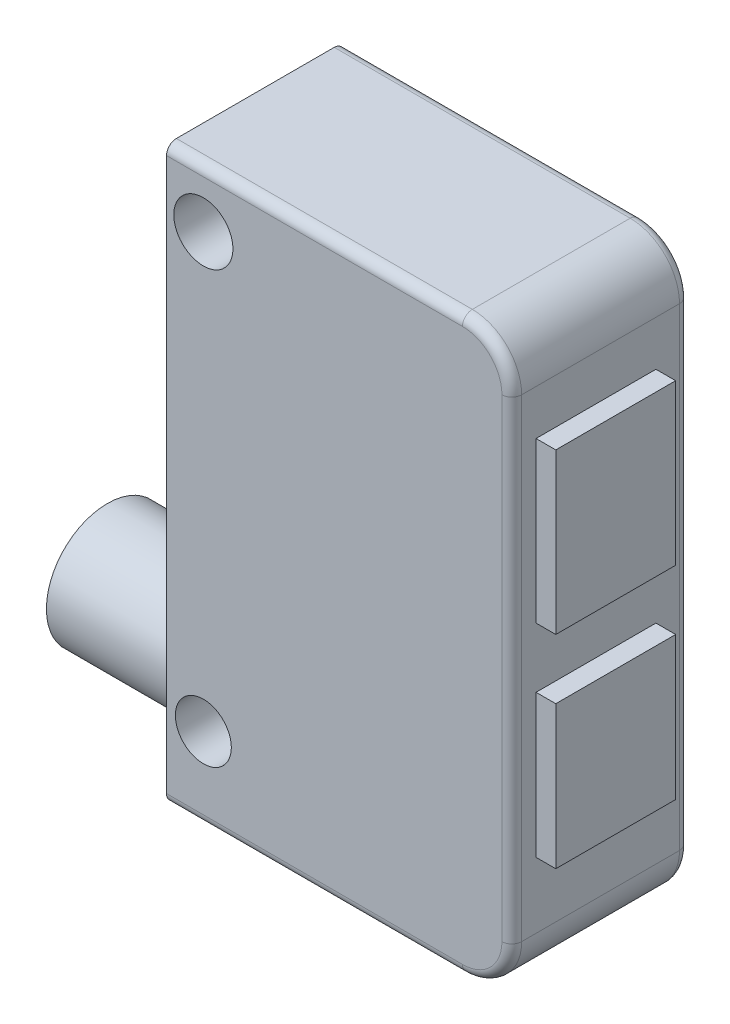
SolidWorks part; units mm, degrees
ref_plane "Alzado" through (0, 0, 0) normal (0, 0, 1) x (1, 0, 0)
ref_plane "Planta" through (0, 0, 0) normal (0, 1, 0) x (1, 0, 0)
ref_plane "Vista lateral" through (0, 0, 0) normal (1, 0, 0) x (0, 0, -1)
sketch "Croquis1" plane through (0, 0, 0) normal (0, 0, 1) x (1, 0, 0)
  line L1 (-17.5, 29) -> (17.5, 29)
  line L2 (-17.5, 29) -> (-17.5, -29)
  line L3 (-17.5, -29) -> (17.5, -29)
  line L4 (17.5, 29) -> (17.5, -29)
  line L5 (-17.5, 29) -> (17.5, -29) construction
  line L6 (-17.5, -29) -> (17.5, 29) construction
  point P0 (0, 0)
  dimension "D1" = 35
  dimension "D2" = 58
extrude "Saliente-Extruir1" add sketch "Croquis1" along normal blind 18
sketch "Croquis2" plane through (-17.5, 0, 0) normal (-1, 0, 0) x (0, 0, 1)
  circle A0 centre (8, -21.7144) radius 6.1719
extrude "Saliente-Extruir2" add sketch "Croquis2" along normal blind 16
fillet "Redondeo1" radius 5 2 edges at (17.5, -29, 9) (17.5, 29, 9)
fillet "Redondeo2" radius 1 10 edges at (-2.5, -29, 0) (16.0355, -27.5355, 0) (17.5, 0, 0) (16.0355, 27.5355, 0) (-2.5, -29, 18) (16.0355, -27.5355, 18) (17.5, 0, 18) (16.0355, 27.5355, 18) (-2.5, 29, 0) (-2.5, 29, 18)
sketch "Croquis3" plane through (0, 0, 18) normal (0, 0, 1) x (1, 0, 0)
  circle A0 centre (-13.7643, 23.1741) radius 2.9977
  circle A1 centre (-13.7643, -20.6814) radius 2.8355
extrude "Cortar-Extruir1" cut sketch "Croquis3" against normal blind 16
sketch "Croquis4" plane through (17.5, 0, 0) normal (1, 0, 0) x (0, 0, -1)
  line L1 (-15.5433, 3.2327) -> (-3.3915, 3.2327)
  line L2 (-15.5433, 3.2327) -> (-15.5433, 19.435)
  line L3 (-15.5433, 19.435) -> (-3.3915, 19.435)
  line L4 (-3.3915, 3.2327) -> (-3.3915, 19.435)
  line L5 (-15.5433, 3.2327) -> (-3.3915, 19.435) construction
  line L6 (-15.5433, 19.435) -> (-3.3915, 3.2327) construction
  line L7 (-15.5433, -17.3319) -> (-3.3915, -17.3319)
  line L8 (-15.5433, -17.3319) -> (-15.5433, -2.8432)
  line L9 (-15.5433, -2.8432) -> (-3.3915, -2.8432)
  line L10 (-3.3915, -17.3319) -> (-3.3915, -2.8432)
  line L11 (-15.5433, -17.3319) -> (-3.3915, -2.8432) construction
  line L12 (-15.5433, -2.8432) -> (-3.3915, -17.3319) construction
  point P0 (-9.4674, 11.3339)
  point P5 (-9.4674, -10.0875)
extrude "Saliente-Extruir3" add sketch "Croquis4" along normal blind 2
